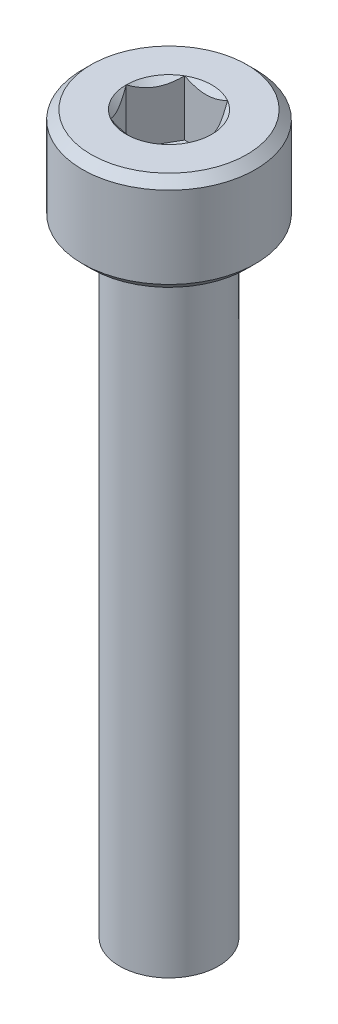
SolidWorks part; units mm, degrees
ref_plane "Front" through (0, 0, 0) normal (0, 0, 1) x (1, 0, 0)
ref_plane "Top" through (0, 0, 0) normal (0, 1, 0) x (1, 0, 0)
ref_plane "Right" through (0, 0, 0) normal (1, 0, 0) x (0, 0, -1)
sketch "Sketch1" plane through (0, 0, 0) normal (0, 1, 0) x (1, 0, 0)
  circle A0 centre (0, 0) radius 3.5
  dimension "D1" = 7
extrude "Boss-Extrude1" add sketch "Sketch1" along normal blind 4
sketch "Sketch2" plane through (0, 4, 0) normal (0, 1, 0) x (1, 0, 0)
  line L1 (0.866, 1.5) -> (-0.866, 1.5)
  line L2 (-0.866, 1.5) -> (-1.7321, 0)
  line L3 (-1.7321, 0) -> (-0.866, -1.5)
  line L4 (-0.866, -1.5) -> (0.866, -1.5)
  line L5 (0.866, -1.5) -> (1.7321, 0)
  line L6 (1.7321, 0) -> (0.866, 1.5)
  circle A0 centre (0, 0) radius 1.5 construction
  point P10 (0, 1.5)
  dimension "D1" = 3
extrude "Cut-Extrude1" cut sketch "Sketch2" against normal blind 2.25
sketch "Sketch3" plane through (0, 4, 0) normal (0, 1, 0) x (1, 0, 0)
  circle A0 centre (0, 0) radius 1.7321
extrude "Cut-Extrude2" cut sketch "Sketch3" against normal through all draft 45
chamfer "Chamfer1" distance 0.35 angle 45 2 edges at (0, 0, 3.5) (0, 4, 3.5)
sketch "草图1" plane through (0, 0, 0) normal (0, -1, 0) x (-1, 0, 0)
  circle A0 centre (0, 0) radius 2
  dimension "D1" = 4
extrude "凸台-拉伸1" add sketch "草图1" along normal blind 25
